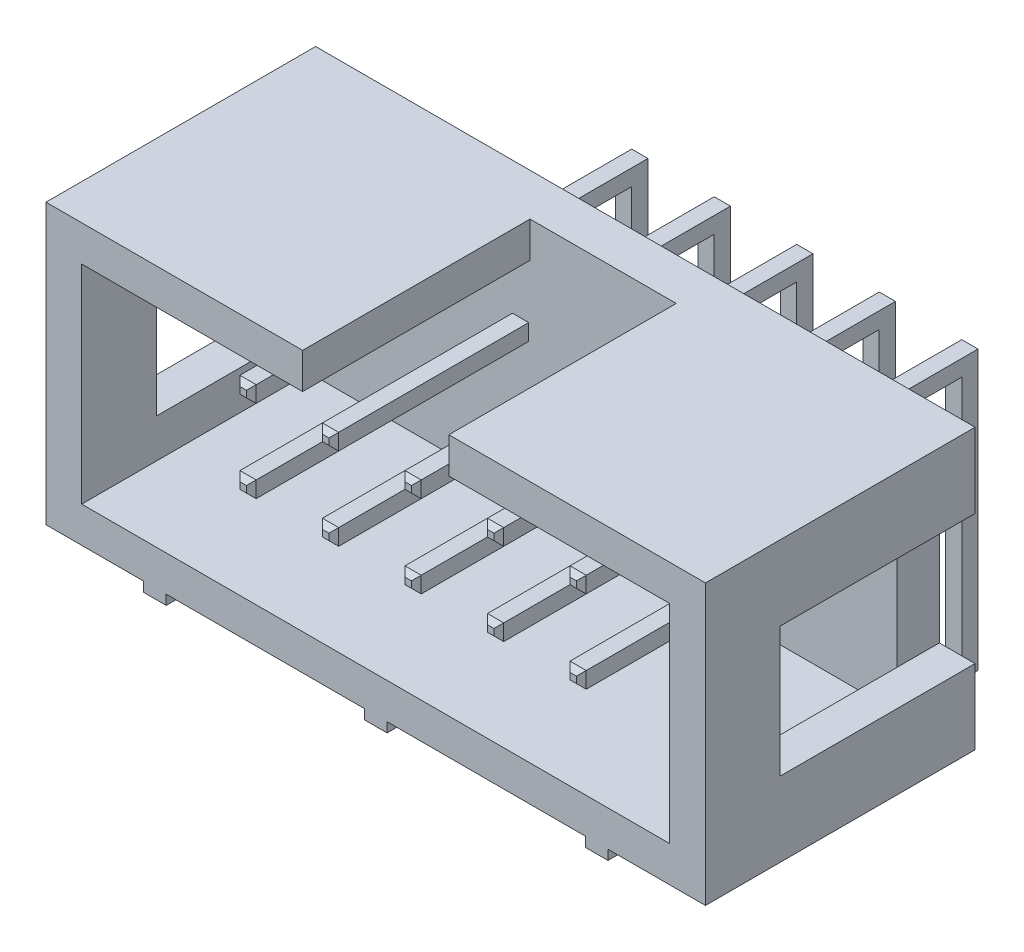
SolidWorks part; units mm, degrees
ref_plane "Přední rovina" through (0, 0, 0) normal (0, 0, 1) x (1, 0, 0)
ref_plane "Horní rovina" through (0, 0, 0) normal (0, 1, 0) x (1, 0, 0)
ref_plane "Pravá rovina" through (0, 0, 0) normal (1, 0, 0) x (0, 0, -1)
sketch "Skica1" plane through (0, 0, 0) normal (0, 0, 1) x (1, 0, 0)
  line L0 (-10.15, -4.3) -> (10.15, 4.3) construction
  line L1 (-10.15, 4.3) -> (10.15, 4.3)
  line L2 (-10.15, 4.3) -> (-10.15, -4.3)
  line L3 (-10.15, -4.3) -> (10.15, -4.3)
  line L4 (10.15, 4.3) -> (10.15, -4.3)
  line L5 (-5.08, 1.27) -> (5.08, -1.27) construction
  line L6 (-5.08, 1.27) -> (5.08, 1.27) construction
  line L7 (-5.08, 1.27) -> (-5.08, -1.27) construction
  line L8 (-5.08, -1.27) -> (5.08, -1.27) construction
  line L9 (5.08, 1.27) -> (5.08, -1.27) construction
  dimension "D1" = 8.6
  dimension "D2" = 5.07
  dimension "D3" = 2.54
extrude "Přidat vysunutím1" add sketch "Skica1" along normal blind 8.3
sketch "Skica2" plane through (0, 0, 8.3) normal (0, 0, 1) x (1, 0, 0)
  line L0 (-9.05, -3.2) -> (9.05, 3.2) construction
  line L1 (-9.05, 3.2) -> (9.05, 3.2)
  line L2 (-9.05, 3.2) -> (-9.05, -3.2)
  line L3 (-9.05, -3.2) -> (9.05, -3.2)
  line L4 (9.05, 3.2) -> (9.05, -3.2)
  line L5 (-9.05, 3.2) -> (-10.15, 3.2) construction
  line L6 (-10.15, 4.3) -> (-10.15, -4.3) construction
  line L7 (-9.05, 3.2) -> (-9.05, 4.3) construction
  line L8 (10.15, 4.3) -> (-10.15, 4.3) construction
  line L9 (-5.08, 1.27) -> (5.08, -1.27) construction
  line L10 (-5.08, 1.27) -> (5.08, 1.27) construction
  line L11 (-5.08, 1.27) -> (-5.08, -1.27) construction
  line L12 (-5.08, -1.27) -> (5.08, -1.27) construction
  line L13 (5.08, 1.27) -> (5.08, -1.27) construction
  line L14 (5.08, -1.27) -> (5.0859, -1.2395) construction
  dimension "D1" = 3.97
  dimension "D2" = 2.54
extrude "Odebrat vysunutím1" cut sketch "Skica2" against normal blind 7
sketch "Skica3" plane through (0, 4.3, 0) normal (0, 1, 0) x (1, 0, 0)
  line L0 (10.15, -8.3) -> (-10.15, -8.3) construction
  line L1 (-2.25, -8.3) -> (2.25, -8.3)
  line L2 (-2.25, -8.3) -> (-2.25, -1.3)
  line L3 (-2.25, -1.3) -> (2.25, -1.3)
  line L4 (2.25, -8.3) -> (2.25, -1.3)
  line L5 (0, 0) -> (0, -4.2387) construction
  line L6 (10.15, 0) -> (-10.15, 0) construction
  line L7 (9.05, -1.3) -> (-9.05, -1.3) construction
  dimension "D1" = 4.5
extrude "Odebrat vysunutím3" cut sketch "Skica3" against normal up to next
sketch "Skica4" plane through (10.15, 0, 0) normal (1, 0, 0) x (0, 0, -1)
  line L0 (0, -4.3) -> (0, 4.3) construction
  line L1 (0, 2) -> (-6, 2)
  line L2 (0, 2) -> (0, -2)
  line L3 (0, -2) -> (-6, -2)
  line L4 (-6, 2) -> (-6, -2)
  line L5 (-6, 0) -> (0, 0) construction
  dimension "D1" = 4
  dimension "D2" = 6
extrude "Odebrat vysunutím4" cut sketch "Skica4" against normal up to surface (19.2 mm away)
mirror "Zrcadlit2" about plane through (0, 0, 0) normal (1, 0, 0) of "Odebrat vysunutím4"
sketch "Skica5" plane through (0, -4.3, 0) normal (0, -1, 0) x (1, 0, 0)
  line L0 (-10.15, 0) -> (10.15, 0) construction
  line L1 (-7.15, 8.3) -> (-6.45, 8.3)
  line L2 (-7.15, 8.3) -> (-7.15, 0)
  line L3 (-7.15, 0) -> (-6.45, 0)
  line L4 (-6.45, 8.3) -> (-6.45, 0)
  line L5 (0, 0) -> (0, 7.714) construction
  line L6 (-0.35, 8.3) -> (0.35, 8.3)
  line L7 (-0.35, 8.3) -> (-0.35, 0)
  line L8 (-0.35, 0) -> (0.35, 0)
  line L9 (0.35, 8.3) -> (0.35, 0)
  line L10 (6.45, 8.3) -> (6.45, 0)
  line L11 (7.15, 0) -> (6.45, 0)
  line L12 (7.15, 8.3) -> (7.15, 0)
  line L13 (7.15, 8.3) -> (6.45, 8.3)
  line L14 (-10.15, 8.3) -> (-10.15, 0) construction
  line L15 (-10.15, 8.3) -> (10.15, 8.3) construction
  dimension "D1" = 0.7
  dimension "D2" = 3
extrude "Přidat vysunutím2" add sketch "Skica5" along normal blind 0.3
ref_plane "Rovina1" through (5.08, 0, 0) normal (1, 0, 0) x (0, 0, -1)
sketch "Skica6" plane through (5.08, 0, 0) normal (1, 0, 0) x (0, 0, -1)
  line L0 (-7.3, 1.27) -> (4.66, 1.27) construction
  line L1 (4.66, 1.27) -> (4.66, -7.2) construction
  line L2 (-7.3, -1.27) -> (2.12, -1.27) construction
  line L4 (2.12, -1.27) -> (2.12, -7.2) construction
  line L5 (0, 0) -> (-16.0264, 0) construction
  line L6 (0, 2) -> (0, -2) construction
  line L7 (-8.3, -4.3) -> (0, -4.3) construction
  line L8 (-8.3, -4.3) -> (-8.3, 4.3) construction
  line L9 (-7.3, 1.02) -> (4.41, 1.02)
  line L10 (4.41, 1.02) -> (4.41, -7.2)
  line L11 (-7.3, 1.52) -> (4.91, 1.52)
  line L12 (4.91, 1.52) -> (4.91, -7.2)
  line L13 (-7.3, -1.52) -> (1.87, -1.52)
  line L14 (1.87, -1.52) -> (1.87, -7.2)
  line L15 (-7.3, -1.02) -> (2.37, -1.02)
  line L16 (2.37, -1.02) -> (2.37, -7.2)
  line L17 (-7.3, 1.52) -> (-7.3, 1.02)
  line L18 (-7.3, -1.02) -> (-7.3, -1.52)
  line L20 (1.87, -7.2) -> (2.37, -7.2)
  line L21 (4.41, -7.2) -> (4.91, -7.2)
  dimension "D1" = 2.54
  dimension "D2" = 2.54
  dimension "D3" = 2.12
  dimension "D4" = 2.9
  dimension "D5" = 1
  dimension "D6" = 0.25
  dimension "D7" = 0.25
  dimension "D8" = 0.25
  dimension "D9" = 0.25
extrude "Přidat vysunutím3" add sketch "Skica6" along normal mid plane 0.5 separate body
chamfer "Zkosení1" distance 0.15 angle 45 8 edges at (5.08, -7.2, -4.41) (5.33, -7.2, -4.66) (5.08, -7.2, -4.91) (4.83, -7.2, -4.66) (5.08, 1.52, 7.3) (5.33, 1.27, 7.3) (5.08, 1.02, 7.3) (4.83, 1.27, 7.3)
chamfer "Zkosení2" distance 0.15 angle 45 8 edges at (5.08, -1.02, 7.3) (5.33, -1.27, 7.3) (5.08, -1.52, 7.3) (4.83, -1.27, 7.3) (5.08, -7.2, -1.87) (5.33, -7.2, -2.12) (5.08, -7.2, -2.37) (4.83, -7.2, -2.12)
pattern_linear "LinPole1" count 5 spacing 2.54 along (-1, 0, 0) of bodies 109 110
equation "\"n\"=10"
equation "\"pins_w\"= 2.54 * int(\"n\" / 2 - 1)"
equation "\"pins_w_half\"= \"pins_w\" / 2"
equation "\"n_half\"= int(\"n\" / 2)"
